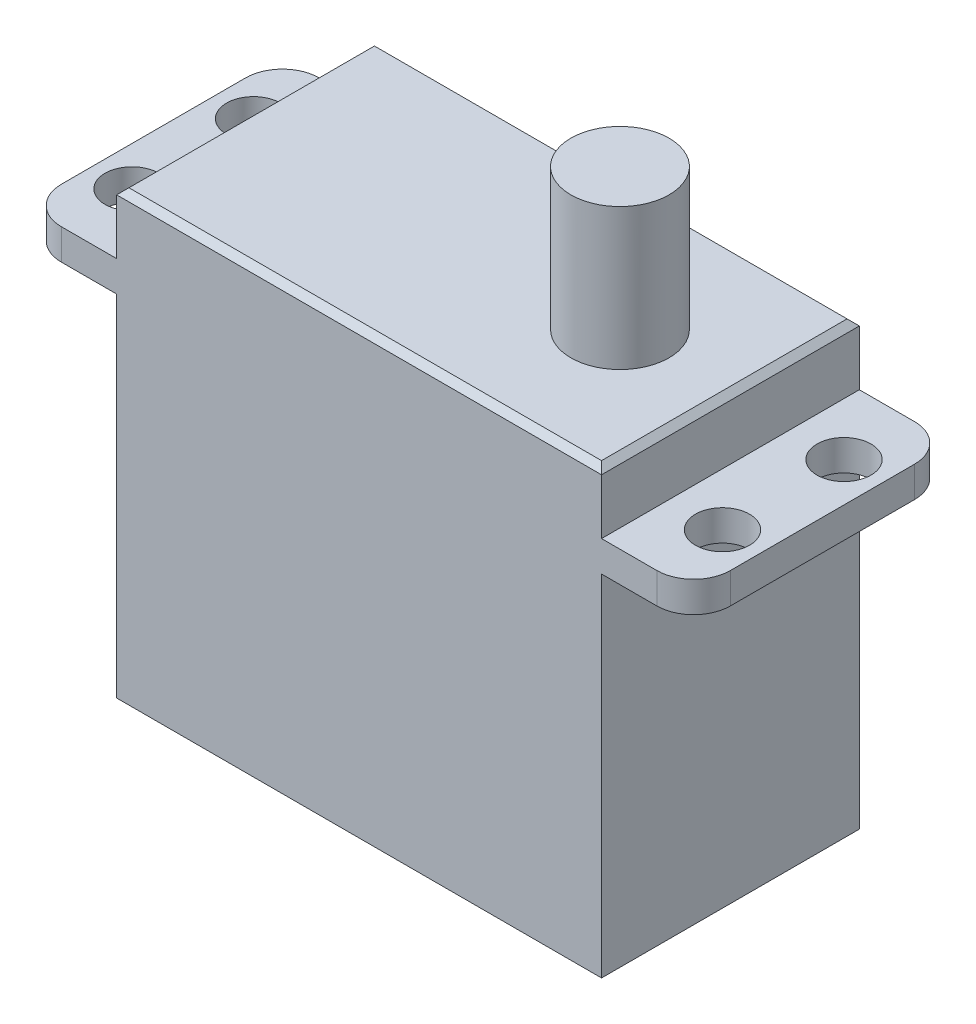
SolidWorks part; units mm, degrees
ref_plane "Front Plane" through (0, 0, 0) normal (0, 0, 1) x (1, 0, 0)
ref_plane "Top Plane" through (0, 0, 0) normal (0, 1, 0) x (1, 0, 0)
ref_plane "Right Plane" through (0, 0, 0) normal (1, 0, 0) x (0, 0, -1)
sketch "Sketch1" plane through (0, 0, 0) normal (0, 1, 0) x (1, 0, 0)
  line L1 (-19.75, -10.5) -> (19.75, -10.5)
  line L2 (-19.75, -10.5) -> (-19.75, 10.5)
  line L3 (-19.75, 10.5) -> (19.75, 10.5)
  line L4 (19.75, -10.5) -> (19.75, 10.5)
  line L5 (-19.75, -10.5) -> (19.75, 10.5) construction
  line L6 (-19.75, 10.5) -> (19.75, -10.5) construction
  point P0 (0, 0)
  dimension "D1" = 21
  dimension "D2" = 39.5
extrude "Boss-Extrude1" add sketch "Sketch1" along normal blind 36
sketch "Sketch2" plane through (0, 36, 0) normal (0, 1, 0) x (1, 0, 0)
  line L2 (19.75, -10.5) -> (19.75, 10.5) construction
  line L3 (-19.75, 0) -> (19.75, 0) construction
  line L4 (-19.75, 10.5) -> (-19.75, -10.5) construction
  circle A0 centre (10.75, 0) radius 4
  dimension "D1" = 8
  dimension "D2" = 9
  dimension "D3" = 0
extrude "Boss-Extrude2" add sketch "Sketch2" along normal blind 11.5
sketch "Sketch4" plane through (19.75, 0, 0) normal (1, 0, 0) x (0, 0, -1)
  line L0 (-10.5, 31) -> (-10.5, 28.5)
  line L1 (-10.5, 31) -> (10.5, 31)
  line L2 (-10.5, 28.5) -> (10.5, 28.5)
  line L3 (10.5, 31) -> (10.5, 28.5)
  line L4 (-10.5, 36) -> (-10.5, 0) construction
  line L5 (10.5, 36) -> (10.5, 0) construction
  line L6 (-10.5, 0) -> (10.5, 0) construction
  dimension "D1" = 28.5
  dimension "D2" = 2.5
extrude "Boss-Extrude4" add sketch "Sketch4" along normal blind 7.5
sketch "Sketch5" plane through (0, 31, 0) normal (0, 1, 0) x (1, 0, 0)
  line L0 (27.25, 0) -> (19.75, 0) construction
  line L1 (27.25, 10.5) -> (27.25, -10.5) construction
  line L2 (19.75, 10.5) -> (19.75, -10.5) construction
  line L3 (19.75, -10.5) -> (19.75, 10.5) construction
  circle A0 centre (24.05, 4.95) radius 2.2
  circle A1 centre (24.05, -4.95) radius 2.2
  dimension "D1" = 4.4
  dimension "D3" = 4.95
  dimension "D4" = 4.3
  dimension "D2" = 9.9
extrude "Cut-Extrude1" cut sketch "Sketch5" against normal blind 7.5
fillet "Fillet1" radius 3 2 edges at (27.25, 29.75, -10.5) (27.25, 29.75, 10.5)
mirror "Mirror1" about plane through (0, 0, 0) normal (1, 0, 0) of "Fillet1", "Cut-Extrude1", "Boss-Extrude4"
chamfer "Chamfer1" distance 0.5 angle 45 4 edges at (-19.75, 36, 0) (0, 36, 10.5) (19.75, 36, 0) (0, 36, -10.5)
